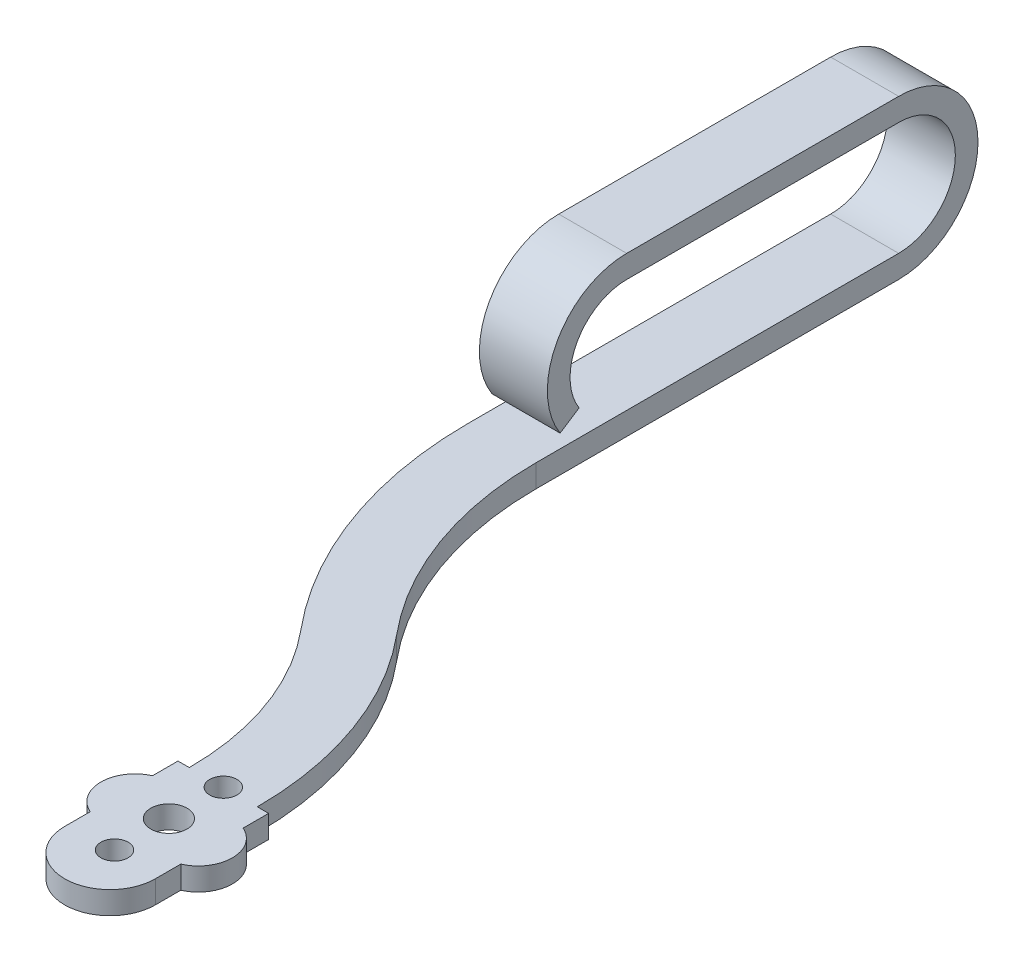
SolidWorks part; units mm, degrees
ref_plane "Piano frontale" through (0, 0, 0) normal (0, 0, 1) x (1, 0, 0)
ref_plane "Piano superiore" through (0, 0, 0) normal (0, 1, 0) x (1, 0, 0)
ref_plane "Piano destro" through (0, 0, 0) normal (1, 0, 0) x (0, 0, -1)
sketch "Schizzo1" plane through (0, 0, 0) normal (-1, 0, 0) x (0, 0, 1)
  line L0 (-80, 35) -> (-20, 35)
  line L1 (0, 0) -> (-80, 0)
  arc A0 (-80, 35) -> (-80, 0) centre (-80, 17.5) ccw
  arc A1 (-20, 35) -> (-5.3031, 8) centre (-20, 17.5) cw
  dimension "D1" = 17.5
  dimension "D2" = 95
  dimension "D5" = 97.5
  dimension "D3" = 35
  dimension "D4" = 8
sketch "Schizzo2" plane through (0, 0, 0) normal (0, 0, -1) x (-1, 0, 0)
  line L1 (-7.5, 0) -> (7.5, 0)
  line L2 (-7.5, 0) -> (-7.5, 5)
  line L3 (-7.5, 5) -> (7.5, 5)
  line L4 (7.5, 0) -> (7.5, 5)
  line L5 (-7.5, 0) -> (7.5, 5) construction
  line L6 (-7.5, 5) -> (7.5, 0) construction
  point P0 (0, 0)
  dimension "D1" = 15
  dimension "D2" = 5
sweep "Sweep1" add profiles "Schizzo2" path "Schizzo1"
sketch "Schizzo3" plane through (0, 0, 0) normal (0, -1, 0) x (1, 0, 0)
  line L0 (42.5, 119.5688) -> (42.5, 96.5) construction
  line L1 (7.5, 0) -> (7.5, -25.9386) construction
  arc A0 (42.5, 96.5) -> (25, 48.25) centre (-32.7661, 96.5) cw
  arc A1 (25, 48.25) -> (7.5, 0) centre (82.7661, 0) ccw
  dimension "D1" = 96.5
  dimension "D2" = 35
sketch "Schizzo5" plane through (0, 0, 0) normal (0, 0, 1) x (1, 0, 0)
  line L4 (-7.5, 5) -> (-7.5, 0)
  line L5 (-7.5, 0) -> (7.5, 0)
  line L6 (7.5, 0) -> (7.5, 5)
  line L7 (7.5, 5) -> (-7.5, 5)
  line L8 (-7.5, 5) -> (-7.5, 0)
  line L9 (-7.5, 0) -> (7.5, 0)
  line L10 (7.5, 0) -> (7.5, 5)
  line L11 (7.5, 5) -> (-7.5, 5)
  dimension "D1" = 0
sweep "Sweep2" add profiles "Schizzo5" path "Schizzo3"
sketch "Schizzo9" plane through (0, 0, 0) normal (0, -1, 0) x (1, 0, 0)
  line L0 (25, 96.5) -> (45, 96.5)
  line L1 (27.5, 96.5) -> (42.5, 96.5) construction
  line L2 (45, 96.5) -> (45, 102.1261)
  line L3 (25, 102.1261) -> (25, 96.5)
  line L4 (35, 96.5) -> (35, 137.0762) construction
  line L6 (25, 115.8739) -> (25, 121.5)
  line L7 (45, 121.5) -> (45, 115.8739)
  arc A0 (45, 102.1261) -> (45, 115.8739) centre (42, 109) ccw
  arc A1 (25, 121.5) -> (45, 121.5) centre (35, 121.5) cw
  arc A2 (25, 115.8739) -> (25, 102.1261) centre (28, 109) ccw
  circle A3 centre (35, 120.5) radius 3
  circle A4 centre (35, 108.5) radius 4
  point P19 (35, 96.5)
  dimension "D3" = 7.5
  dimension "D5" = 12
  dimension "D6" = 12
  dimension "D8" = 20
  dimension "D9" = 29
  dimension "D7" = 8
  dimension "D1" = 6
  dimension "D2" = 20
  dimension "D4" = 35
extrude "Estrusione-Estrusione1" add sketch "Schizzo9" against normal up to vertex (5 mm away) up to point (27.5, 5, 96.5)
sketch "Schizzo10" plane through (0, 5, 0) normal (0, 1, 0) x (1, 0, 0)
  line L0 (35, -96.5) -> (35, -108.5) construction
  circle A0 centre (35, -96.5) radius 3
  circle A2 centre (35, -120.5) radius 3 construction
  dimension "D2" = 12
extrude "Taglio-Estrusione1" cut sketch "Schizzo10" against normal through all
